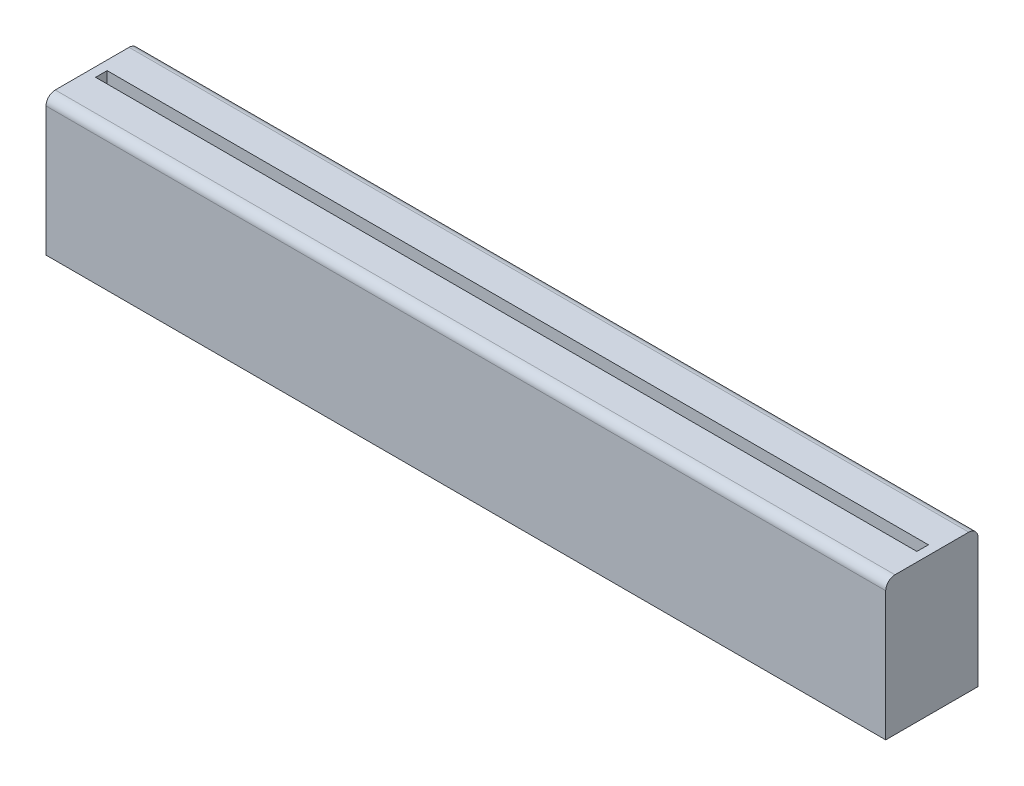
SolidWorks part; units mm, degrees
ref_plane "Front Plane" through (0, 0, 0) normal (0, 0, 1) x (1, 0, 0)
ref_plane "Top Plane" through (0, 0, 0) normal (0, 1, 0) x (1, 0, 0)
ref_plane "Right Plane" through (0, 0, 0) normal (1, 0, 0) x (0, 0, -1)
sketch "Sketch1" plane through (0, 0, 0) normal (1, 0, 0) x (0, 0, -1)
  line L0 (12.7, 0) -> (-12.7, 0)
  line L1 (-12.7, 0) -> (-12.7, 35.56)
  line L2 (-10.16, 38.1) -> (-1.5875, 38.1)
  line L4 (-6.35, 2.54) -> (6.35, 2.54)
  line L5 (0, 2.54) -> (0, 0)
  line L8 (-1.5875, 38.1) -> (-1.5875, 7.62)
  line L9 (-1.5875, 7.62) -> (-6.35, 7.62)
  line L10 (-6.35, 7.62) -> (-6.35, 2.54)
  line L11 (1.5875, 7.62) -> (6.35, 7.62)
  line L12 (1.5875, 38.1) -> (1.5875, 7.62)
  line L15 (10.16, 38.1) -> (1.5875, 38.1)
  line L16 (12.7, 0) -> (12.7, 35.56)
  line L17 (6.35, 7.62) -> (6.35, 2.54)
  line L18 (10.16, 35.56) -> (4.1275, 35.56)
  line L19 (4.1275, 35.56) -> (4.1275, 10.16)
  line L20 (4.1275, 10.16) -> (8.89, 10.16)
  line L22 (-8.89, 0) -> (8.89, 0)
  line L24 (-4.1275, 10.16) -> (-8.89, 10.16)
  line L25 (-4.1275, 35.56) -> (-4.1275, 10.16)
  line L26 (-10.16, 35.56) -> (-4.1275, 35.56)
  line L27 (-10.16, 2.54) -> (-10.16, 35.56)
  line L29 (10.16, 2.54) -> (10.16, 35.56)
  line L30 (-8.89, 10.16) -> (-8.89, 0) construction
  line L31 (10.16, 2.54) -> (-10.16, 2.54) construction
  line L32 (8.89, 10.16) -> (8.89, 0) construction
  line L33 (-8.89, 10.16) -> (-8.89, 2.54)
  line L34 (-8.89, 2.54) -> (-10.16, 2.54)
  line L35 (8.89, 10.16) -> (8.89, 2.54)
  line L36 (8.89, 2.54) -> (10.16, 2.54)
  arc A0 (10.16, 38.1) -> (12.7, 35.56) centre (10.16, 35.56) cw
  arc A1 (-12.7, 35.56) -> (-10.16, 38.1) centre (-10.16, 35.56) cw
  arc A2 (-10.16, 35.56) -> (-10.16, 35.56) centre (-10.16, 35.56) cw
  arc A3 (10.16, 35.56) -> (10.16, 35.56) centre (10.16, 35.56) cw
  point P3 (0, 0)
  point P19 (12.7, 38.1)
  point P22 (-12.7, 38.1)
  point P40 (0, 0)
  dimension "D6" = 2.54
  dimension "D1" = 38.1
  dimension "D2" = 5.08
  dimension "D3" = 2.54
  dimension "D4" = 6.35
  dimension "D5" = 1.5875
  dimension "D7" = 2.54
  dimension "D8" = 12.7
extrude "Boss-Extrude1" add sketch "Sketch1" along normal mid plane 228.6 contours L11 L17 L4 L5 L0 L16 L15 L12 | L10 L9 L8 L2 L1 L0 L5 L4
sketch "Sketch2" plane through (0, 0, 0) normal (1, 0, 0) x (0, 0, -1)
  line L0 (-12.7, 0) -> (12.7, 0)
  line L1 (12.7, 0) -> (12.7, 35.56)
  line L2 (10.16, 38.1) -> (-10.16, 38.1)
  line L3 (-12.7, 35.56) -> (-12.7, 0)
  line L4 (-10.16, 38.1) -> (-1.5875, 38.1) construction
  arc A0 (12.7, 35.56) -> (10.16, 38.1) centre (10.16, 35.56) ccw
  arc A1 (-10.16, 38.1) -> (-12.7, 35.56) centre (-10.16, 35.56) ccw
  dimension "D1" = 2.54
extrude "Boss-Extrude2" add sketch "Sketch2" along normal mid plane 2.54 from surface at 114.3 starting at face at (114.3, 18.5809, 0)
sketch "Sketch4" plane through (-114.3, 0, 0) normal (-1, 0, 0) x (0, 0, 1)
  line L0 (-12.7, 0) -> (12.7, 0)
  line L1 (12.7, 0) -> (12.7, 35.56)
  line L2 (10.16, 38.1) -> (-10.16, 38.1)
  line L3 (-12.7, 35.56) -> (-12.7, 0)
  line L5 (1.5875, 38.1) -> (-1.5875, 38.1) construction
  line L8 (-6.35, 7.62) -> (6.35, 7.62)
  line L9 (-6.35, 7.62) -> (-6.35, 2.54)
  line L10 (-6.35, 2.54) -> (6.35, 2.54)
  line L11 (6.35, 7.62) -> (6.35, 2.54)
  arc A0 (12.7, 35.56) -> (10.16, 38.1) centre (10.16, 35.56) ccw
  arc A1 (-10.16, 38.1) -> (-12.7, 35.56) centre (-10.16, 35.56) ccw
  dimension "D1" = 2.54
extrude "Boss-Extrude4" add sketch "Sketch4" along normal mid plane 2.54
